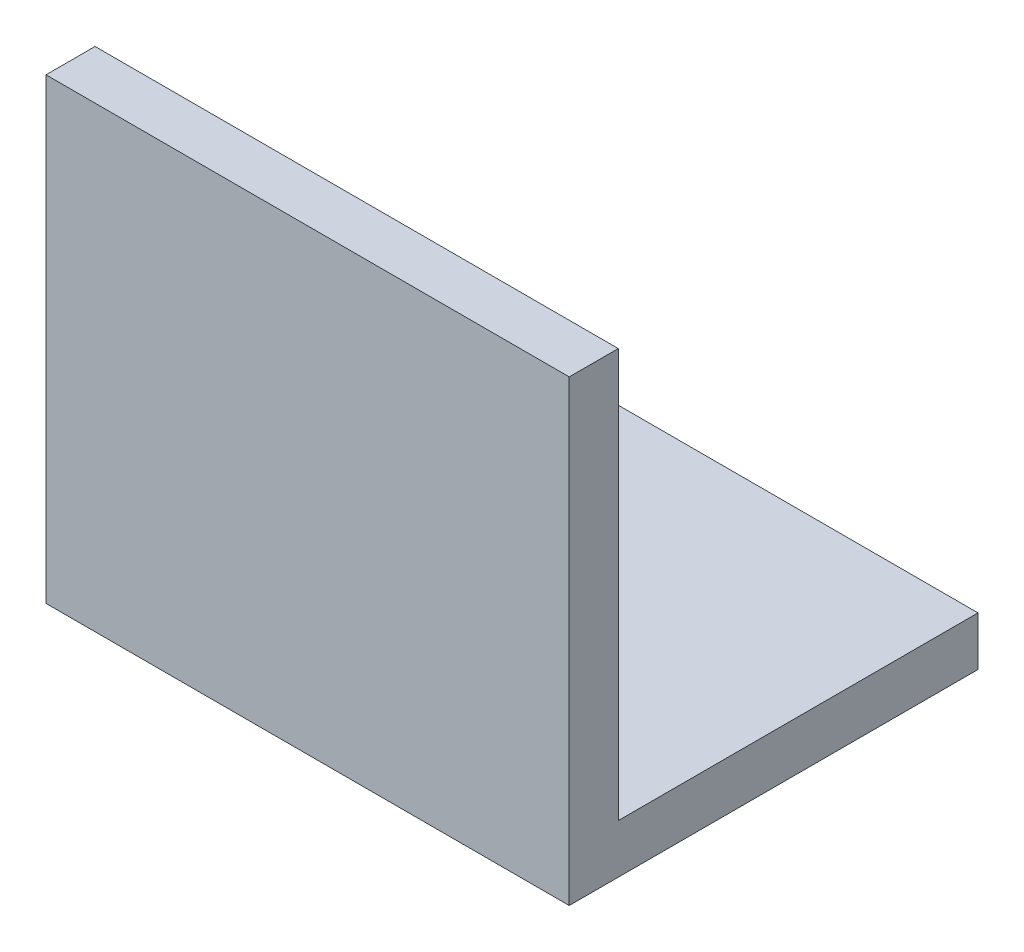
SolidWorks part; units mm, degrees
ref_plane "Alzado" through (0, 0, 0) normal (0, 0, 1) x (1, 0, 0)
ref_plane "Planta" through (0, 0, 0) normal (0, 1, 0) x (1, 0, 0)
ref_plane "Vista lateral" through (0, 0, 0) normal (1, 0, 0) x (0, 0, -1)
sketch "Croquis1" plane through (0, 0, 0) normal (0, 0, 1) x (1, 0, 0)
  line L1 (8, -7) -> (-8, -7)
  line L2 (8, -7) -> (8, 7)
  line L3 (8, 7) -> (-8, 7)
  line L4 (-8, -7) -> (-8, 7)
  line L5 (8, -7) -> (-8, 7) construction
  line L6 (8, 7) -> (-8, -7) construction
  point P0 (0, 0)
extrude "Saliente-Extruir1" add sketch "Croquis1" along normal blind 1.5
sketch "Croquis2" plane through (0, 0, 0) normal (0, 0, -1) x (-1, 0, 0)
  line L0 (8, 7) -> (8, -7) construction
  line L1 (-8, -7) -> (8, -7)
  line L2 (-8, -7) -> (-8, -5.5)
  line L3 (-8, -5.5) -> (8, -5.5)
  line L4 (8, -7) -> (8, -5.5)
extrude "Saliente-Extruir2" add sketch "Croquis2" along normal blind 11
